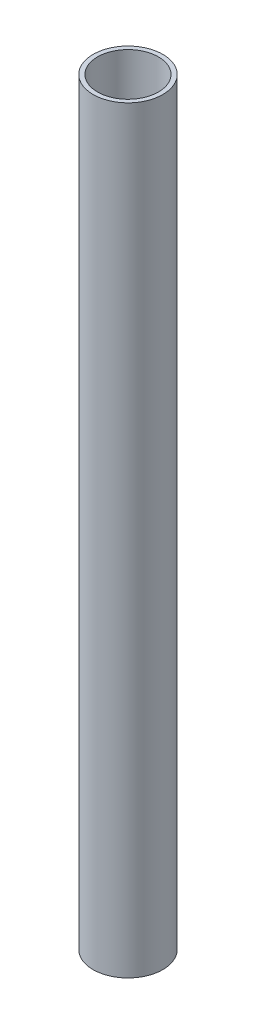
SolidWorks part; units mm, degrees
material "7079 Alloy"
ref_plane "Front Plane" through (0, 0, 0) normal (0, 0, 1) x (1, 0, 0)
ref_plane "Top Plane" through (0, 0, 0) normal (0, 1, 0) x (1, 0, 0)
ref_plane "Right Plane" through (0, 0, 0) normal (1, 0, 0) x (0, 0, -1)
sketch "Sketch1" plane through (0, 0, 0) normal (0, 1, 0) x (1, 0, 0)
  circle A0 centre (0, 0) radius 8
  circle A1 centre (0, 0) radius 7
  dimension "D1" = 16
  dimension "D2" = 1
extrude "Boss-Extrude1" add sketch "Sketch1" along normal blind 174.1
